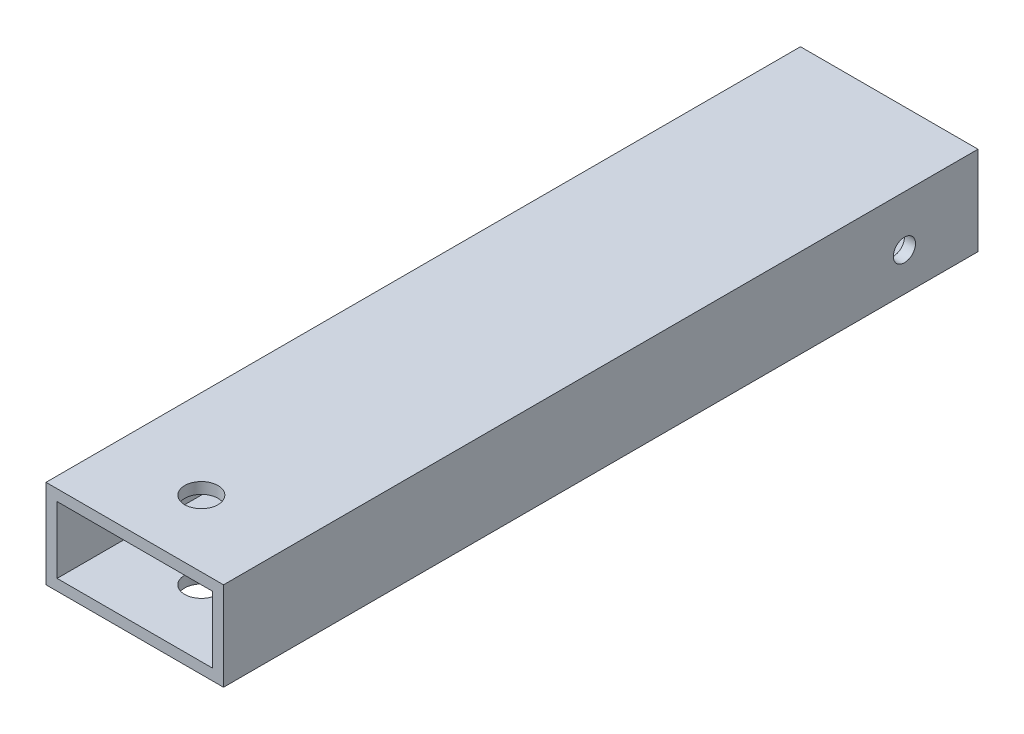
SolidWorks part; units mm, degrees
ref_plane "Front Plane" through (0, 0, 0) normal (0, 0, 1) x (1, 0, 0)
ref_plane "Top Plane" through (0, 0, 0) normal (0, 1, 0) x (1, 0, 0)
ref_plane "Right Plane" through (0, 0, 0) normal (1, 0, 0) x (0, 0, -1)
sketch "Sketch1" plane through (0, 0, 0) normal (0, 0, 1) x (1, 0, 0)
  line L0 (-22.225, -9.525) -> (22.225, -9.525)
  line L1 (-25.4, -12.7) -> (25.4, -12.7)
  line L2 (-25.4, -12.7) -> (-25.4, 12.7)
  line L3 (-25.4, 12.7) -> (25.4, 12.7)
  line L4 (25.4, -12.7) -> (25.4, 12.7)
  line L5 (22.225, -9.525) -> (22.225, 9.525)
  line L6 (-22.225, 9.525) -> (22.225, 9.525)
  line L7 (-22.225, -9.525) -> (-22.225, 9.525)
  dimension "D1" = 25.4
  dimension "D2" = 50.8
  dimension "D3" = 3.175
extrude "Boss-Extrude1" add sketch "Sketch1" along normal blind 304.8
sketch "Sketch2" plane through (0, 12.7, 0) normal (0, 1, 0) x (1, 0, 0)
  line L0 (0, -304.8) -> (0, -285.75) construction
  line L1 (25.4, -304.8) -> (-25.4, -304.8) construction
  circle A0 centre (0, -285.75) radius 4.7625
  dimension "D2" = 9.525
  dimension "D1" = 19.05
extrude "Cut-Extrude1" cut sketch "Sketch2" against normal through all
sketch "Sketch3" plane through (-25.4, 0, 0) normal (-1, 0, 0) x (0, 0, 1)
  circle A1 centre (109.9476, -1.7398) radius 3.175
extrude "Cut-Extrude2" cut sketch "Sketch3" against normal through all
sketch "Sketch4" plane through (0, 0, 0) normal (0, 0, -1) x (-1, 0, 0)
  line L4 (-25.4, 12.7) -> (-25.4, -12.7)
  line L5 (-25.4, -12.7) -> (25.4, -12.7)
  line L6 (25.4, -12.7) -> (25.4, 12.7)
  line L7 (25.4, 12.7) -> (-25.4, 12.7)
  line L8 (-25.4, 12.7) -> (-25.4, -12.7)
  line L9 (-25.4, -12.7) -> (25.4, -12.7)
  line L10 (25.4, -12.7) -> (25.4, 12.7)
  line L11 (25.4, 12.7) -> (-25.4, 12.7)
  dimension "D1" = 0
extrude "Cut-Extrude3" cut sketch "Sketch4" against normal blind 88.9
